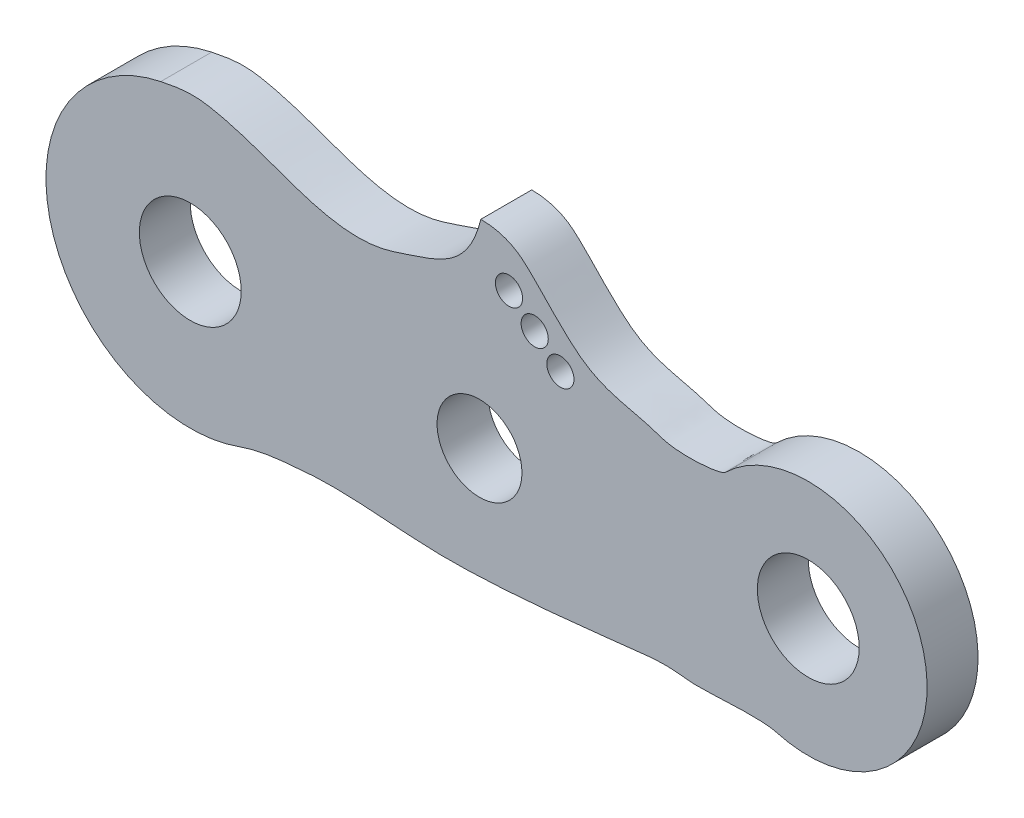
SolidWorks part; units mm, degrees
ref_plane "Front Plane" through (0, 0, 0) normal (0, 0, 1) x (1, 0, 0)
ref_plane "Top Plane" through (0, 0, 0) normal (0, 1, 0) x (1, 0, 0)
ref_plane "Right Plane" through (0, 0, 0) normal (1, 0, 0) x (0, 0, -1)
sketch "Sketch1" plane through (0, 0, 0) normal (0, 0, 1) x (1, 0, 0)
  line L0 (0, 0) -> (15, 0)
  line L1 (0, 0) -> (180.0763, 0)
  line L3 (167, 0) -> (182, 0)
  line L4 (90.5491, 42.4088) -> (118.7069, 18.1018)
  line L6 (132.5588, 19.0828) -> (213.6203, -204.977) construction
  arc A0 (-8.6924, 41.6016) -> (14.4531, -39.967) centre (0, 0) ccw
  arc A1 (172.6134, -33.7178) -> (157.5904, 25.0833) centre (182, 0) ccw
  circle A2 centre (0, 0) radius 15
  circle A3 centre (182, 0) radius 15
  circle A8 centre (85.181, -5) radius 12.5
  circle A9 centre (93.8634, 39.5478) radius 4
  circle A10 centre (101.433, 33.0133) radius 4
  circle A11 centre (109.0027, 26.4788) radius 4
  spline S0 degree 3 poles (14.4531, -39.967) (20.3242, -37.8438) (27.7278, -37.215) (43.4726, -35.8338) (58.3976, -37.2764) (84.9463, -38.5832) (114.7045, -35.5222) (142.3557, -32.1714) (144.5674, -33.69) (153.9297, -33.4754) (168.5908, -32.598) (172.6134, -33.7178) knots 0 0 0 0 0.112559 0.148247 0.333694 0.39262 0.678585 0.734325 0.894275 0.922842 1 1 1 1
  spline S1 degree 3 poles (-8.6924, 41.6016) (-2.6494, 42.8642) (1.6545, 43.2803) (17.706, 39.7892) (32.678, 32.9044) (51.2365, 29.5015) (71.8518, 36.5494) (82.0422, 39.1312) (85.5767, 53.6155) knots 0 0 0 0 0.135926 0.178704 0.427785 0.654064 0.711286 1 1 1 1
  spline S2 degree 3 poles (85.5767, 53.6155) (89.9511, 53.5978) (95.066, 51.9584) (103.617, 44.4315) (117.0311, 27.9519) (131.2047, 27.3588) (143.4334, 22.7091) (156.1776, 23.7084) (157.5904, 25.0833) knots 0 0 0 0 0.13386 0.17954 0.456794 0.762139 0.816459 1 1 1 1
  dimension "D1" = 85
  dimension "D2" = 70
  dimension "D3" = 182
  dimension "D4" = 30
  dimension "D5" = 30
  dimension "D6" = 5
  dimension "D7" = 25
  dimension "D8" = 8
  dimension "D9" = 8
  dimension "D10" = 8
  dimension "D11" = 8
  dimension "D12" = 10
  dimension "D13" = 10
extrude "Boss-Extrude1" add sketch "Sketch1" along normal blind 15
